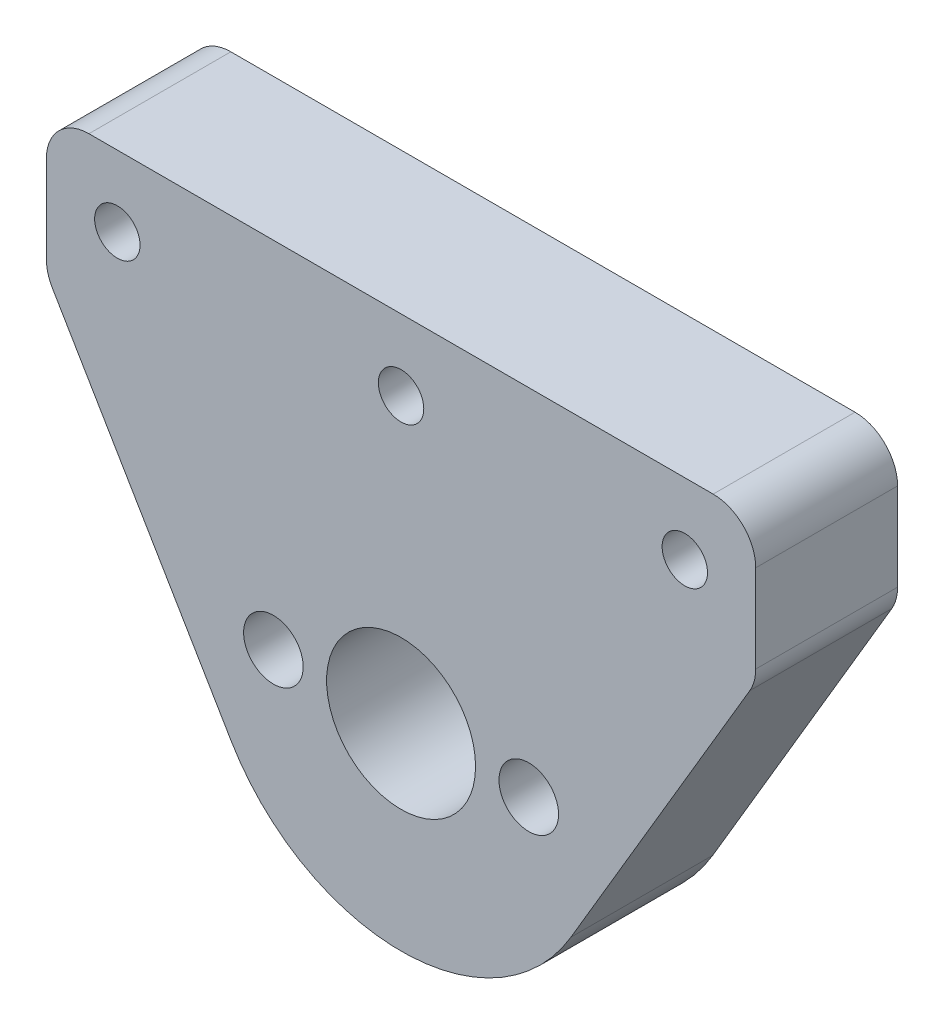
SolidWorks part; units mm, degrees
material "1060 合金"
ref_plane "正面" through (0, 0, 0) normal (0, 0, 1) x (1, 0, 0)
ref_plane "平面" through (0, 0, 0) normal (0, 1, 0) x (1, 0, 0)
ref_plane "右側面" through (0, 0, 0) normal (1, 0, 0) x (0, 0, -1)
sketch "ｽｹｯﾁ1" plane through (0, 0, 0) normal (0, 0, 1) x (1, 0, 0)
  line L0 (0, 0) -> (-20, 0) construction
  line L1 (0, 0) -> (0, -20) construction
  line L2 (-25, -5) -> (-11.969, -27.0677)
  line L3 (25, 5) -> (-25, 5)
  line L4 (25, 5) -> (25, -5)
  line L5 (25, -5) -> (-25, -5)
  line L6 (-25, 5) -> (-25, -5)
  line L7 (25, 5) -> (-25, -5) construction
  line L8 (25, -5) -> (-25, 5) construction
  line L9 (25, -5) -> (11.969, -27.0677)
  circle A0 centre (0, 0) radius 1.6
  circle A1 centre (-20, 0) radius 1.6
  circle A2 centre (0, -20) radius 13.9
  circle A3 centre (20, 0) radius 1.6
  circle A4 centre (0, -20) radius 9 construction
  circle A5 centre (-9, -20) radius 2.1
  circle A6 centre (9, -20) radius 2.1
  point P13 (-25, 0)
  dimension "D1" = 3.2
  dimension "D3" = 3.2
  dimension "D5" = 27.8
  dimension "D7" = 5
  dimension "D8" = 18
  dimension "D9" = 4.2
  dimension "D2" = 20
  dimension "D4" = 20
  dimension "D6" = 5
extrude "ﾎﾞｽ - 押し出し1" add sketch "ｽｹｯﾁ1" along normal blind 10 contours A2 A5 A6 | A2 L9 L5 L2 | L3 L6 L5 L4 A0 A1 A3
fillet "ﾌｨﾚｯﾄ1" radius 3 4 edges at (-25, -5, 5) (-25, 5, 5) (25, 5, 5) (25, -5, 5)
sketch "ｽｹｯﾁ2" plane through (0, 0, 10) normal (0, 0, 1) x (1, 0, 0)
  line L0 (-9, -20) -> (9, -20) construction
  circle A0 centre (0, -20) radius 5.25
  dimension "D1" = 10.5
extrude "ｶｯﾄ - 押し出し1" cut sketch "ｽｹｯﾁ2" against normal through all contours A0
